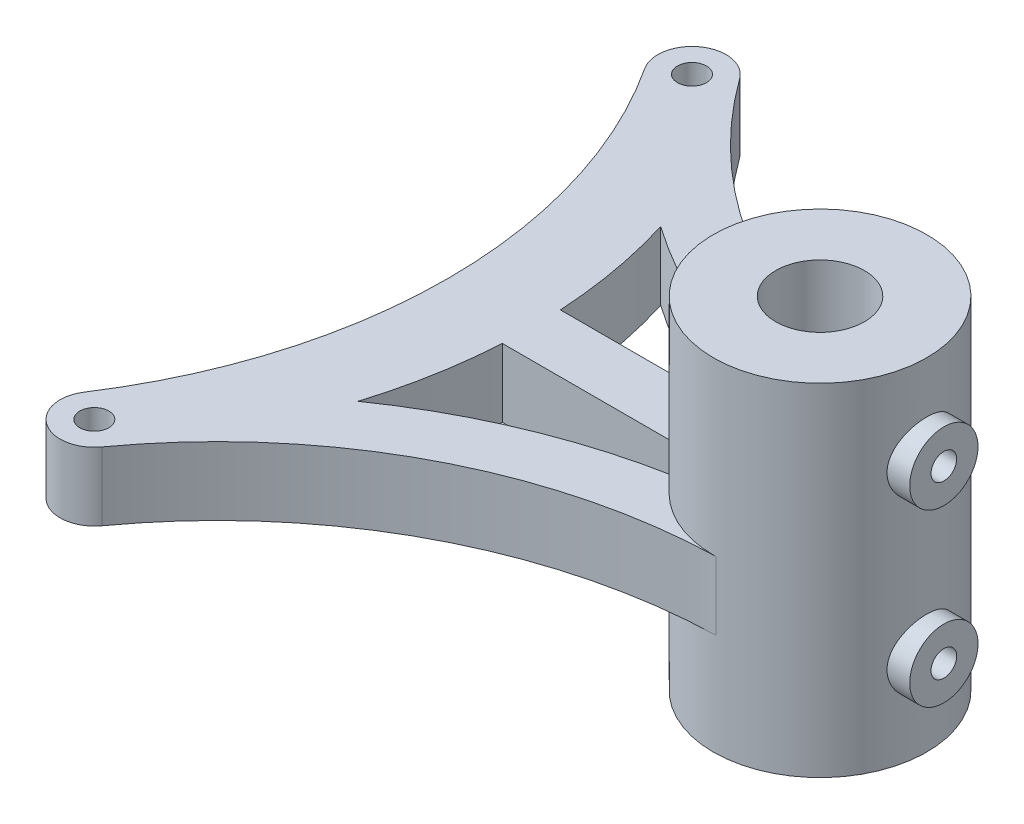
SolidWorks part; units mm, degrees
material "Custom Plastic"
ref_plane "Front Plane" through (0, 0, 0) normal (0, 0, 1) x (1, 0, 0)
ref_plane "Top Plane" through (0, 0, 0) normal (0, 1, 0) x (1, 0, 0)
ref_plane "Right Plane" through (0, 0, 0) normal (1, 0, 0) x (0, 0, -1)
sketch "Sketch1" plane through (0, 0, 0) normal (0, 1, 0) x (1, 0, 0)
  line L0 (0, 0) -> (29.8839, 0) construction
  line L1 (-0.4922, -3.4) -> (21.2905, -3.4)
  line L2 (0, -3.4) -> (29.8839, -3.4) construction
  line L3 (-0.4922, 3.4) -> (21.2905, 3.4)
  circle A0 centre (-16.6808, 35) radius 1.7
  circle A1 centre (-16.6808, -35) radius 1.7
  arc A2 (-13.4383, 37.3422) -> (-20.0297, 32.8125) centre (-16.6808, 35) ccw
  arc A3 (-20.0297, -32.8125) -> (-13.4383, -37.3422) centre (-16.6808, -35) ccw
  circle A4 centre (33.3192, 0) radius 5.2
  arc A6 (22.8484, 6.8274) -> (21.2905, 3.4) centre (33.3192, 0) ccw
  arc A8 (-20.0297, -32.8125) -> (-20.0297, 32.8125) centre (-70.2625, 0) ccw
  arc A9 (-3.0745, -17.7277) -> (-0.4922, -3.4) centre (-60.3958, 0) ccw
  arc A10 (33.6434, -12.4958) -> (-13.4383, -37.3422) centre (35.1996, -72.4756) ccw
  arc A11 (33.6434, 12.4958) -> (-13.4383, 37.3422) centre (35.1996, 72.4756) cw
  arc A12 (22.8484, -6.8274) -> (-3.0745, -17.7277) centre (35.1996, -72.4756) ccw
  arc A13 (22.8484, 6.8274) -> (-3.0745, 17.7277) centre (35.1996, 72.4756) cw
  arc A14 (33.467, 5.6981) -> (-18.9506, 33.3604) centre (35.1996, 72.4756) cw construction
  arc A15 (33.6434, -12.4958) -> (33.6434, 12.4958) centre (33.3192, 0) ccw
  arc A16 (-3.0745, 17.7277) -> (-0.4922, 3.4) centre (-60.3958, 0) cw
  arc A17 (21.2905, -3.4) -> (22.8484, -6.8274) centre (33.3192, 0) ccw
  dimension "D2" = 3.4
  dimension "D3" = 3.4
  dimension "D5" = 8
  dimension "D6" = 8
  dimension "D7" = 10.4
  dimension "D8" = 25
  dimension "D9" = 120
  dimension "D10" = 120
  dimension "D11" = 120
  dimension "D1" = 70
  dimension "D4" = 50
  dimension "D12" = 3.4
  dimension "D13" = 6.8
extrude "Boss-Extrude1" add sketch "Sketch1" along normal blind 8
sketch "Sketch2" plane through (0, 8, 0) normal (0, 1, 0) x (1, 0, 0)
  circle A0 centre (33.3192, 0) radius 5.2
  circle A1 centre (33.3192, 0) radius 12.5
  dimension "D1" = 10.4
  dimension "D2" = 25
extrude "Boss-Extrude2" add sketch "Sketch2" along normal mid plane 40
ref_plane "Plane1" through (45.8192, 0, 0) normal (1, 0, 0) x (0, 0, -1)
sketch "Sketch3" plane through (45.8192, 0, 0) normal (1, 0, 0) x (0, 0, -1)
  line L1 (12.5, 28) -> (-12.5, 28) construction
  circle A0 centre (0, -2) radius 1.5
  circle A1 centre (0, -2) radius 4
  circle A2 centre (0, 18) radius 4
  circle A3 centre (0, 18) radius 1.5
  point P3 (0, 0)
  dimension "D1" = 3
  dimension "D2" = 8
  dimension "D3" = 20
  dimension "D4" = 10
extrude "Boss-Extrude3" add sketch "Sketch3" against normal up to surface (0.0903 mm away)
sketch "Sketch4" plane through (45.8192, 0, 0) normal (1, 0, 0) x (0, 0, -1)
  circle A0 centre (0, -2) radius 1.5
  circle A1 centre (0, -2) radius 4
  circle A2 centre (0, 18) radius 4
  circle A3 centre (0, 18) radius 1.5
  dimension "D1" = 8
  dimension "D2" = 3
  dimension "D3" = 20
extrude "Boss-Extrude4" add sketch "Sketch4" along normal blind 2
sketch "Sketch8" plane through (45.8192, 0, 0) normal (1, 0, 0) x (0, 0, -1)
  circle A0 centre (0, -2) radius 1.5
  circle A1 centre (0, 18) radius 1.5
extrude "Cut-Extrude4" cut sketch "Sketch8" against normal up to surface (7.521 mm away) contours A0 | A1
